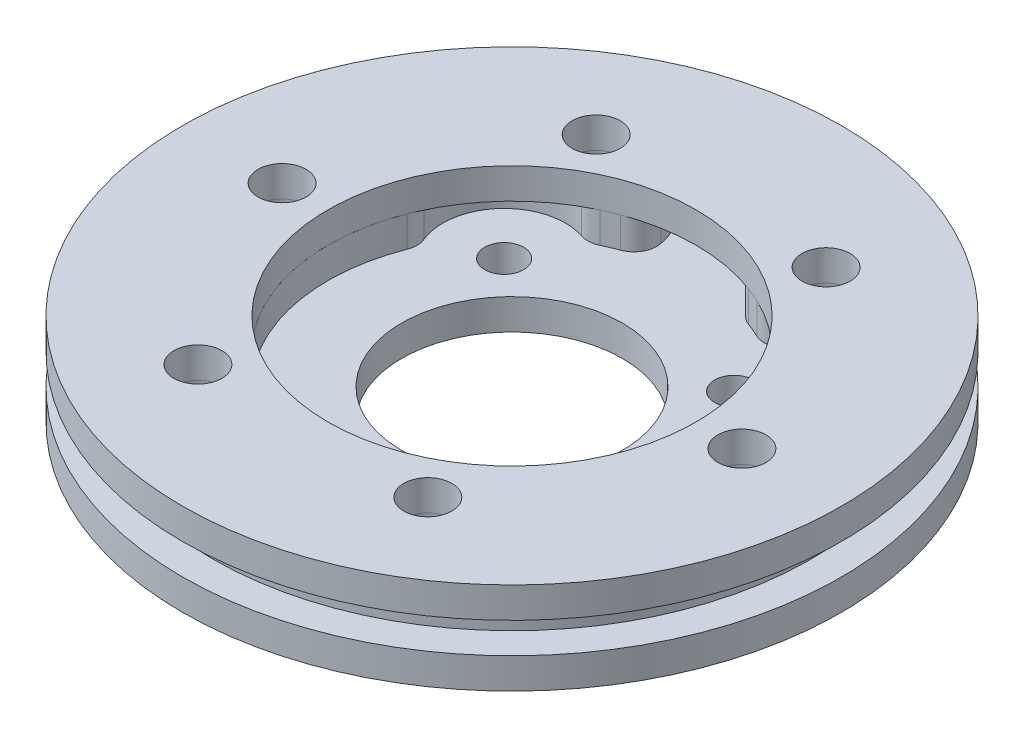
SolidWorks part; units mm, degrees
material "6061-T6 (SS)"
ref_plane "Front Plane" through (0, 0, 0) normal (0, 0, 1) x (1, 0, 0)
ref_plane "Top Plane" through (0, 0, 0) normal (0, 1, 0) x (1, 0, 0)
ref_plane "Right Plane" through (0, 0, 0) normal (1, 0, 0) x (0, 0, -1)
sketch "Sketch1" plane through (0, 0, 0) normal (0, 1, 0) x (1, 0, 0)
  line L0 (0, 0) -> (0, 30.9562) construction
  line L1 (23.8125, 0) -> (11.9062, 20.6222) construction
  line L2 (11.9062, 20.6222) -> (-11.9063, 20.6222) construction
  line L3 (-11.9063, 20.6222) -> (-23.8125, 0) construction
  line L4 (-23.8125, 0) -> (-11.9062, -20.6222) construction
  line L5 (-11.9062, -20.6222) -> (11.9063, -20.6222) construction
  line L6 (11.9063, -20.6222) -> (23.8125, 0) construction
  line L7 (-12.9213, 19.05) -> (12.9213, 19.05) construction
  circle A0 centre (0, 0) radius 30.9562
  circle A1 centre (0, 0) radius 19.05
  circle A2 centre (0, 0) radius 23.8125 construction
  circle A3 centre (0, 0) radius 20.6222 construction
  circle A4 centre (23.8125, 0) radius 2.4892
  circle A5 centre (11.9062, 20.6222) radius 2.4892
  circle A6 centre (-11.9063, 20.6222) radius 2.4892
  circle A7 centre (-23.8125, 0) radius 2.4892
  circle A8 centre (-11.9062, -20.6222) radius 2.4892
  circle A9 centre (11.9063, -20.6222) radius 2.4892
  arc A10 (-17.3769, 25.619) -> (-5.0122, 18.3788) centre (-12.9213, 19.05) cw
  arc A11 (17.3769, 25.619) -> (5.0122, 18.3788) centre (12.9213, 19.05) ccw
  dimension "D1" = 38.1
  dimension "D2" = 61.9125
  dimension "D3" = 47.625
  dimension "D4" = 4.9784
  dimension "D5" = 7.9375
extrude "Boss-Extrude1" add sketch "Sketch1" against normal blind 3.175 contours A0 A11 A1 A10 A9 A8 A7 A6 A5 A4
sketch "Sketch2" plane through (0, -3.175, 0) normal (0, -1, 0) x (-1, 0, 0)
  circle A0 centre (23.8125, 0) radius 2.4892 construction
  circle A1 centre (11.9063, 20.6222) radius 2.4892 construction
  circle A2 centre (11.9062, -20.6222) radius 2.4892 construction
  circle A3 centre (-11.9063, -20.6222) radius 2.4892 construction
  circle A4 centre (-23.8125, 0) radius 2.4892 construction
  circle A5 centre (-11.9062, 20.6222) radius 2.4892 construction
  circle A6 centre (0, 0) radius 34.1313
  circle A18 centre (-11.9062, 20.6222) radius 2.4892
  circle A19 centre (-23.8125, 0) radius 2.4892
  circle A20 centre (-11.9063, -20.6222) radius 2.4892
  circle A21 centre (11.9062, -20.6222) radius 2.4892
  circle A22 centre (11.9063, 20.6222) radius 2.4892
  circle A23 centre (23.8125, 0) radius 2.4892
  circle A24 centre (0, 0) radius 11.43
  circle A25 centre (11.9063, 11.0972) radius 2.0193
  circle A26 centre (-11.9062, 11.0972) radius 2.0193
  dimension "D1" = 22.86
  dimension "D3" = 68.2625
  dimension "D4" = 4.0386
  dimension "D2" = 9.525
extrude "Boss-Extrude2" add sketch "Sketch2" along normal blind 3.175 separate body contours A6
sketch "Sketch3" plane through (0, 0, 0) normal (0, 1, 0) x (1, 0, 0)
  circle A0 centre (-11.9063, 11.0972) radius 6.35
  circle A1 centre (11.9062, 11.0972) radius 6.35
  dimension "D1" = 12.7
extrude "Cut-Extrude1" cut sketch "Sketch3" against normal up to surface (3.175 mm away) up to face at (0, -3.175, -34.1313)
sketch "Sketch4" plane through (0, 0, 0) normal (0, 1, 0) x (1, 0, 0)
  circle A0 centre (0, 0) radius 34.1313 construction
  circle A1 centre (0, 0) radius 34.1313
  circle A2 centre (0, 0) radius 19.05
  arc A3 (-17.3599, 7.8445) -> (17.3599, 7.8445) centre (0, 0) ccw construction
  circle A4 centre (11.9062, 20.6222) radius 2.4892 construction
  circle A5 centre (23.8125, 0) radius 2.4892 construction
  circle A6 centre (11.9063, -20.6222) radius 2.4892 construction
  circle A7 centre (-11.9062, -20.6222) radius 2.4892 construction
  circle A8 centre (-23.8125, 0) radius 2.4892 construction
  circle A9 centre (-11.9063, 20.6222) radius 2.4892 construction
  circle A10 centre (11.9062, 20.6222) radius 2.4892
  circle A11 centre (23.8125, 0) radius 2.4892
  circle A12 centre (11.9063, -20.6222) radius 2.4892
  circle A13 centre (-11.9062, -20.6222) radius 2.4892
  circle A14 centre (-23.8125, 0) radius 2.4892
  circle A15 centre (-11.9063, 20.6222) radius 2.4892
extrude "Boss-Extrude3" add sketch "Sketch4" along normal blind 3.175 separate body
fillet "Fillet2" radius 2.3813 6 edges at (-5.0122, -1.5875, -18.3788) (5.0122, -1.5875, -18.3788) (17.3599, -1.5875, -7.8445) (9.0447, -1.5875, -16.7659) (-9.0447, -1.5875, -16.7659) (-17.3599, -1.5875, -7.8445)
